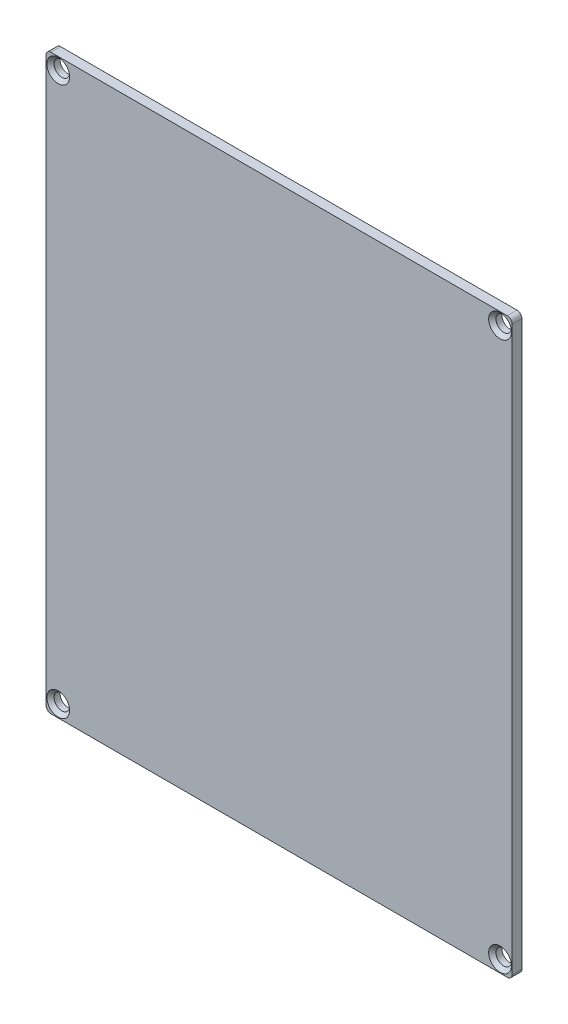
SolidWorks part; units mm, degrees
ref_plane "Ebene vorne" through (0, 0, 0) normal (0, 0, 1) x (1, 0, 0)
ref_plane "Ebene oben" through (0, 0, 0) normal (0, 1, 0) x (1, 0, 0)
ref_plane "Ebene rechts" through (0, 0, 0) normal (1, 0, 0) x (0, 0, -1)
sketch "Skizze1" plane through (0, 0, 0) normal (0, 0, 1) x (1, 0, 0)
  line L1 (-48, -59) -> (48, -59)
  line L2 (-48, -59) -> (-48, 59)
  line L3 (-48, 59) -> (48, 59)
  line L4 (48, -59) -> (48, 59)
  line L5 (-48, -59) -> (48, 59) construction
  line L6 (-48, 59) -> (48, -59) construction
  circle A0 centre (-45.5, 56.5) radius 1.6
  circle A1 centre (45.5, 56.5) radius 1.6
  circle A2 centre (45.5, -56.5) radius 1.6
  circle A3 centre (-45.5, -56.5) radius 1.6
  point P0 (0, 0)
  dimension "D1" = 2.5
  dimension "D11" = 3.2
  dimension "D12" = 3.2
  dimension "D13" = 3.2
  dimension "D14" = 3.2
  dimension "D2" = 96
  dimension "D3" = 118
  dimension "D4" = 2.5
  dimension "D5" = 2.5
  dimension "D6" = 2.5
  dimension "D7" = 2.5
  dimension "D8" = 2.5
  dimension "D9" = 2.5
  dimension "D10" = 2.5
extrude "Aufsatz-Linear austragen2" add sketch "Skizze1" along normal blind 2
chamfer "Fase2" distance 0.75 angle 45 4 edges at (47.1, -56.5, 2) (-43.9, -56.5, 2) (-43.9, 56.5, 2) (47.1, 56.5, 2)
fillet "Verrundung2" radius 1 4 edges at (-48, -59, 1) (48, -59, 1) (48, 59, 1) (-48, 59, 1)
